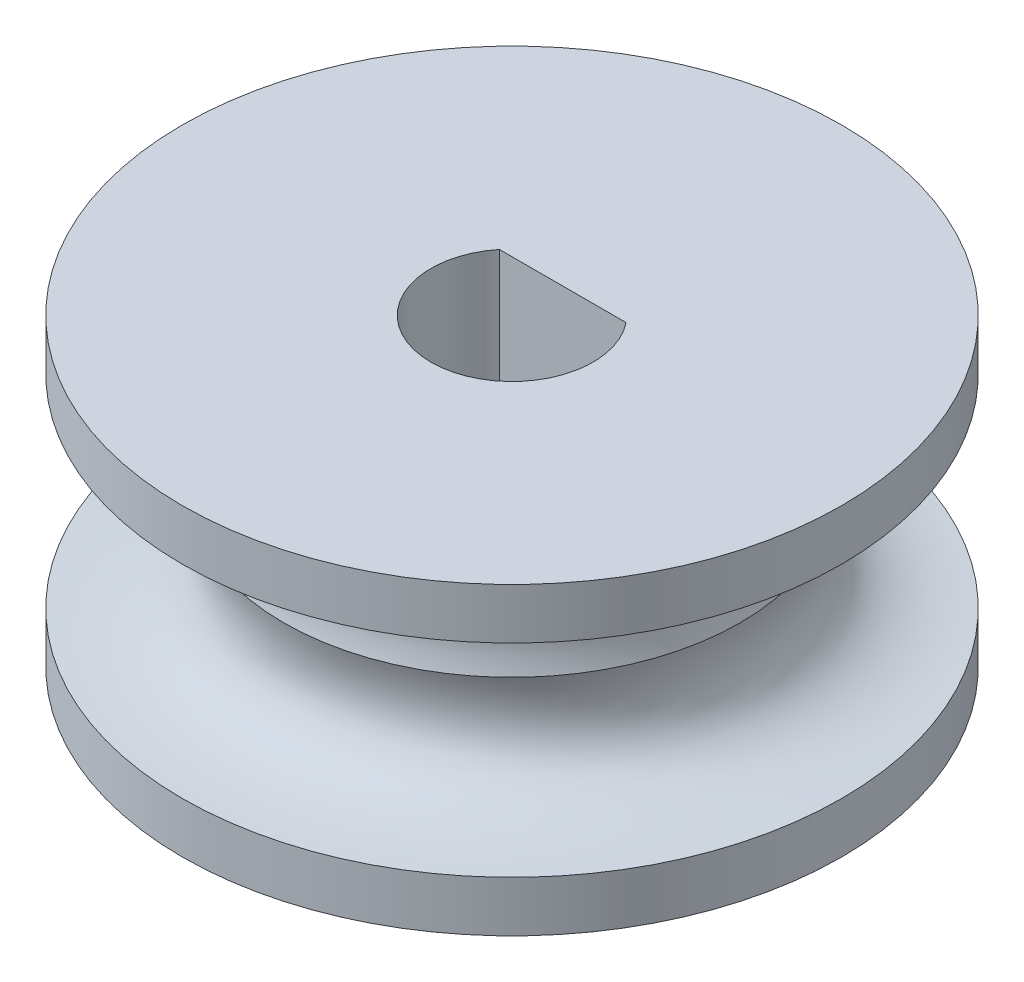
SolidWorks part; units mm, degrees
ref_plane "Front Plane" through (0, 0, 0) normal (0, 0, 1) x (1, 0, 0)
ref_plane "Top Plane" through (0, 0, 0) normal (0, 1, 0) x (1, 0, 0)
ref_plane "Right Plane" through (0, 0, 0) normal (1, 0, 0) x (0, 0, -1)
sketch "Sketch1" plane through (0, 0, 0) normal (0, 0, 1) x (1, 0, 0)
  line L0 (0, 0) -> (-6.5, 0)
  line L1 (-6.5, -1) -> (-6.5, 0)
  line L2 (-4.5, -3) -> (0, -3)
  line L3 (0, -3) -> (0, 0)
  spline S0 degree 3 poles (-4.5, -3) (-4.0026, -1.2546) (-5.5153, -1.0472) (-6.5, -1) knots 0 0 0 0 1 1 1 1
  dimension "D3" = 2
  dimension "D1" = 6.5
  dimension "D2" = 1
  dimension "D4" = 3
revolve "Revolve1" add sketch "Sketch1" angle 360 about L3
mirror "Mirror1" about plane through (-4.5, -3, 0) normal (0, 1, 0) of "Revolve1"
sketch "Sketch2" plane through (0, 0, 0) normal (0, 1, 0) x (1, 0, 0)
  line L0 (-1.249, 1) -> (1.249, 1)
  arc A0 (-1.249, 1) -> (1.249, 1) centre (0, 0) ccw
  arc A1 (1.249, 1) -> (-1.249, 1) centre (0, 0) ccw construction
  dimension "D1" = 3.2
  dimension "D2" = 1
extrude "Cut-Extrude1" cut sketch "Sketch2" along normal through all from surface at -6 starting at face at (0, -6, -6.5)
